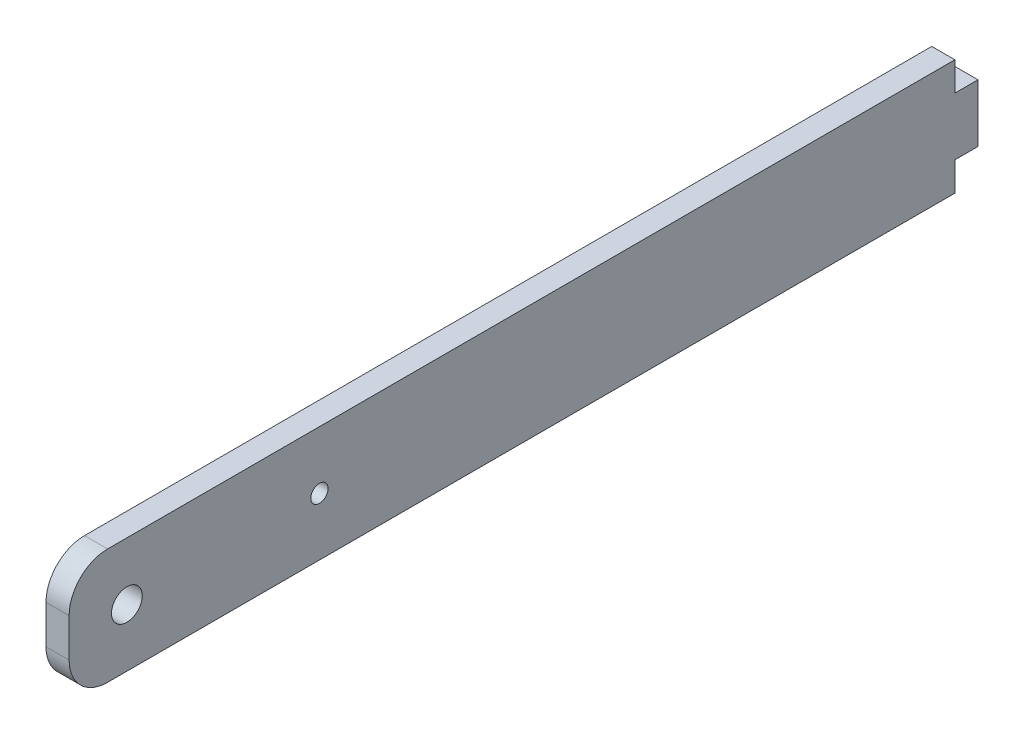
SolidWorks part; units mm, degrees
material "6061-T6 (SS)"
ref_plane "Alzado" through (0, 0, 0) normal (0, 0, 1) x (1, 0, 0)
ref_plane "Planta" through (0, 0, 0) normal (0, 1, 0) x (1, 0, 0)
ref_plane "Vista lateral" through (0, 0, 0) normal (1, 0, 0) x (0, 0, -1)
sketch "Croquis2" plane through (0, 0, 0) normal (1, 0, 0) x (0, 0, -1)
  line L2 (-100, 0) -> (100, 0) construction
  line L3 (-115, 15) -> (115, 15)
  line L4 (-115, 15) -> (-115, -15)
  line L5 (115, 15) -> (115, -15)
  line L6 (115, -15) -> (-115, -15)
  circle A2 centre (-100, 0) radius 4
  circle A3 centre (100, 0) radius 4 construction
  point P3 (-115, 0)
  point P4 (0, 0)
  point P7 (0, 15)
  dimension "D1" = 8
  dimension "D2" = 200
  dimension "D6" = 8
  dimension "D3" = 30
  dimension "D4" = 15
extrude "Saliente-Extruir1" add sketch "Croquis2" along normal mid plane 6
sketch "Croquis5" plane through (3, 0, 0) normal (1, 0, 0) x (0, 0, -1)
  line L0 (115, -15) -> (115, 15) construction
  line L1 (115, 7.5) -> (121, 7.5)
  line L2 (115, 7.5) -> (115, -7.5)
  line L3 (115, -7.5) -> (121, -7.5)
  line L4 (121, 7.5) -> (121, -7.5)
  point P6 (121, 0)
  dimension "D1" = 6
  dimension "D2" = 15
extrude "Saliente-Extruir2" add sketch "Croquis5" against normal through all
hole_wizard "Taladro de margen para M41" positions "Croquis3" profile "Croquis4" hole size "M4" standard "Ansi Metric" end condition up to next
sketch "Croquis3" plane through (3, 0, 0) normal (1, 0, 0) x (0, 0, -1)
  point P0 (-50, 0)
  dimension "D1" = 50
sketch "Croquis4" plane through (3, 0, 50) normal (0, 1, 0) x (0, 0, -1)
  line L0 (0, 0) -> (0, 6)
  line L1 (0, 6) -> (2.25, 6)
  line L2 (2.25, 6) -> (2.25, 0)
  line L5 (2.25, 0) -> (0, 0)
  line L11 (0, -6.35) -> (0, 107.95) construction
  dimension "Diámetro de taladro hasta el siguiente" = 4.5
  dimension "Profundidad de taladro hasta el siguiente" = 6
fillet "Redondeo1" radius 10 2 edges at (0, -15, 115) (0, 15, 115)
